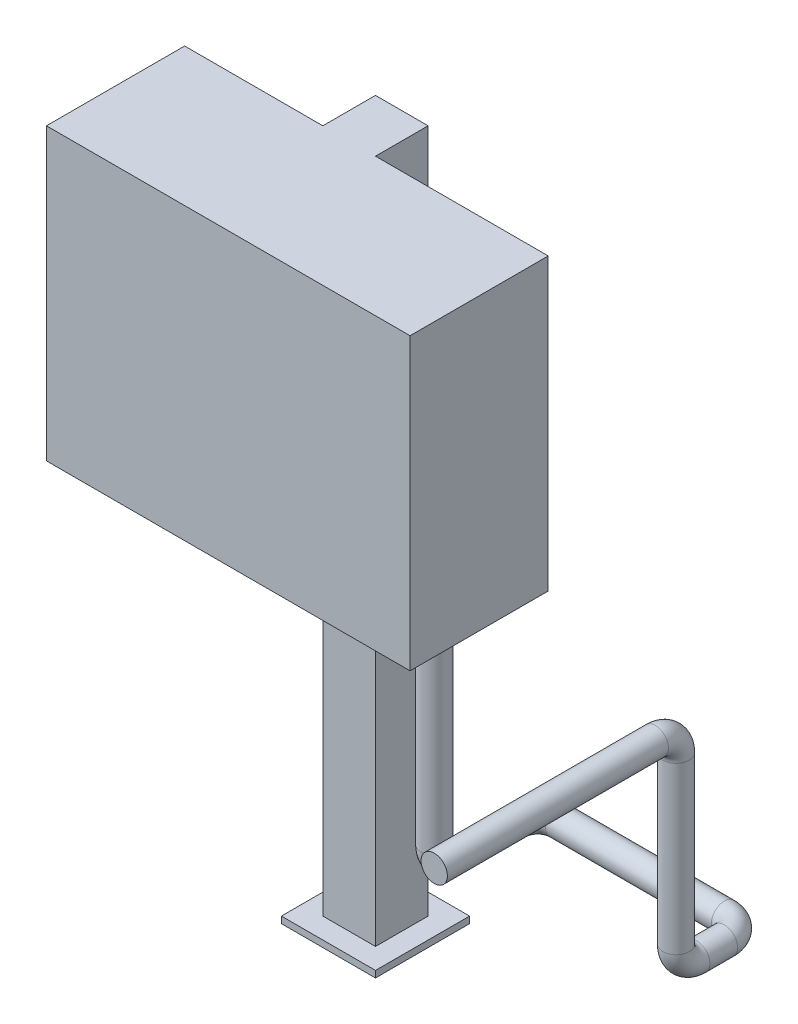
SolidWorks part; units mm, degrees
ref_plane "Alzado" through (0, 0, 0) normal (0, 0, 1) x (1, 0, 0)
ref_plane "Planta" through (0, 0, 0) normal (0, 1, 0) x (1, 0, 0)
ref_plane "Vista lateral" through (0, 0, 0) normal (1, 0, 0) x (0, 0, -1)
sketch "Croquis1" plane through (0, 0, 0) normal (0, 0, 1) x (1, 0, 0)
  line L1 (0, 0) -> (76.2, 0)
  line L2 (0, 0) -> (0, 1000)
  line L3 (0, 1000) -> (76.2, 1000)
  line L4 (76.2, 0) -> (76.2, 1000)
  dimension "D1" = 1000
  dimension "D2" = 76.2
extrude "Saliente-Extruir1" add sketch "Croquis1" along normal blind 76.2
sketch "Croquis2" plane through (0, 0, 0) normal (0, -1, 0) x (1, 0, 0)
  line L0 (38.1, 76.2) -> (38.1, 0) construction
  line L1 (0, 76.2) -> (76.2, 76.2) construction
  line L2 (0, 0) -> (76.2, 0) construction
  line L3 (76.2, 76.2) -> (76.2, 0) construction
  line L4 (106.2, -30) -> (-30, -30)
  line L5 (106.2, -30) -> (106.2, 106.2)
  line L6 (106.2, 106.2) -> (-30, 106.2)
  line L7 (-30, -30) -> (-30, 106.2)
  line L8 (106.2, -30) -> (-30, 106.2) construction
  line L9 (106.2, 106.2) -> (-30, -30) construction
  point P6 (38.1, 38.1)
  dimension "D1" = 30
  dimension "D2" = 30
extrude "Saliente-Extruir2" add sketch "Croquis2" against normal blind 9.525
sketch "Croquis3" plane through (0, 0, 76.2) normal (0, 0, 1) x (1, 0, 0)
  line L0 (0, 1000) -> (0, 9.525) construction
  line L1 (-200, 1000) -> (326.2, 1000)
  line L2 (-200, 1000) -> (-200, 580)
  line L3 (-200, 580) -> (326.2, 580)
  line L4 (326.2, 1000) -> (326.2, 580)
  line L5 (76.2, 9.525) -> (76.2, 1000) construction
  line L6 (76.2, 1000) -> (0, 1000) construction
  dimension "D1" = 200
  dimension "D2" = 250
  dimension "D3" = 420
  dimension "D4" = 0
extrude "Saliente-Extruir3" add sketch "Croquis3" along normal blind 200
sketch "Croquis4" plane through (0, 580, 0) normal (0, -1, 0) x (1, 0, 0)
  line L0 (326.2, 276.2) -> (326.2, 76.2) construction
  line L1 (-200, 276.2) -> (326.2, 276.2) construction
  circle A0 centre (261.2, 176.2) radius 19.05
  dimension "D1" = 38.1
  dimension "D3" = 100
  dimension "D2" = 65
extrude "Saliente-Extruir4" add sketch "Croquis4" along normal blind 30
sketch3d "Croquis3D1"
  line L0 (261.2, 550, 176.2) -> (261.2, 280, 176.2)
  line L1 (261.2, 550, 176.2) -> (261.2, 580, 176.2) construction
  line L2 (261.2, 250, 146.2) -> (261.2, 250, 56.2)
  line L3 (291.2, 250, 26.2) -> (531.2, 250, 26.2)
  line L4 (561.2, 250, 56.2) -> (561.2, 250, 96.2)
  line L5 (561.2, 280, 126.2) -> (561.2, 520, 126.2)
  line L6 (561.2, 550, 156.2) -> (561.2, 550, 476.2)
  arc A0 (561.2, 520, 126.2) -> (561.2, 550, 156.2) centre (561.2, 520, 156.2) ccw
  arc A1 (561.2, 250, 96.2) -> (561.2, 280, 126.2) centre (561.2, 280, 96.2) ccw
  arc A2 (531.2, 250, 26.2) -> (561.2, 250, 56.2) centre (531.2, 250, 56.2) ccw
  arc A3 (261.2, 250, 56.2) -> (291.2, 250, 26.2) centre (291.2, 250, 56.2) ccw
  arc A4 (261.2, 280, 176.2) -> (261.2, 250, 146.2) centre (261.2, 280, 146.2) ccw
  point P11 (561.2, 550, 126.2)
  point P12 (591.2, 520, 156.2)
  point P15 (561.2, 250, 126.2)
  point P16 (531.2, 280, 96.2)
  point P19 (561.2, 250, 26.2)
  point P20 (531.2, 220, 56.2)
  point P23 (261.2, 250, 26.2)
  point P24 (291.2, 220, 56.2)
  point P27 (261.2, 250, 176.2)
  point P28 (291.2, 280, 146.2)
  dimension "D7" = 30
  dimension "D1" = 300
  dimension "D2" = 150
  dimension "D3" = 300
  dimension "D4" = 100
  dimension "D5" = 300
  dimension "D6" = 350
sketch "Croquis5" plane through (0, 550, 0) normal (0, -1, 0) x (1, 0, 0)
  circle A0 centre (261.2, 176.2) radius 19.05
sweep "Barrer1" add profiles "Croquis5" path "Croquis3D1"
